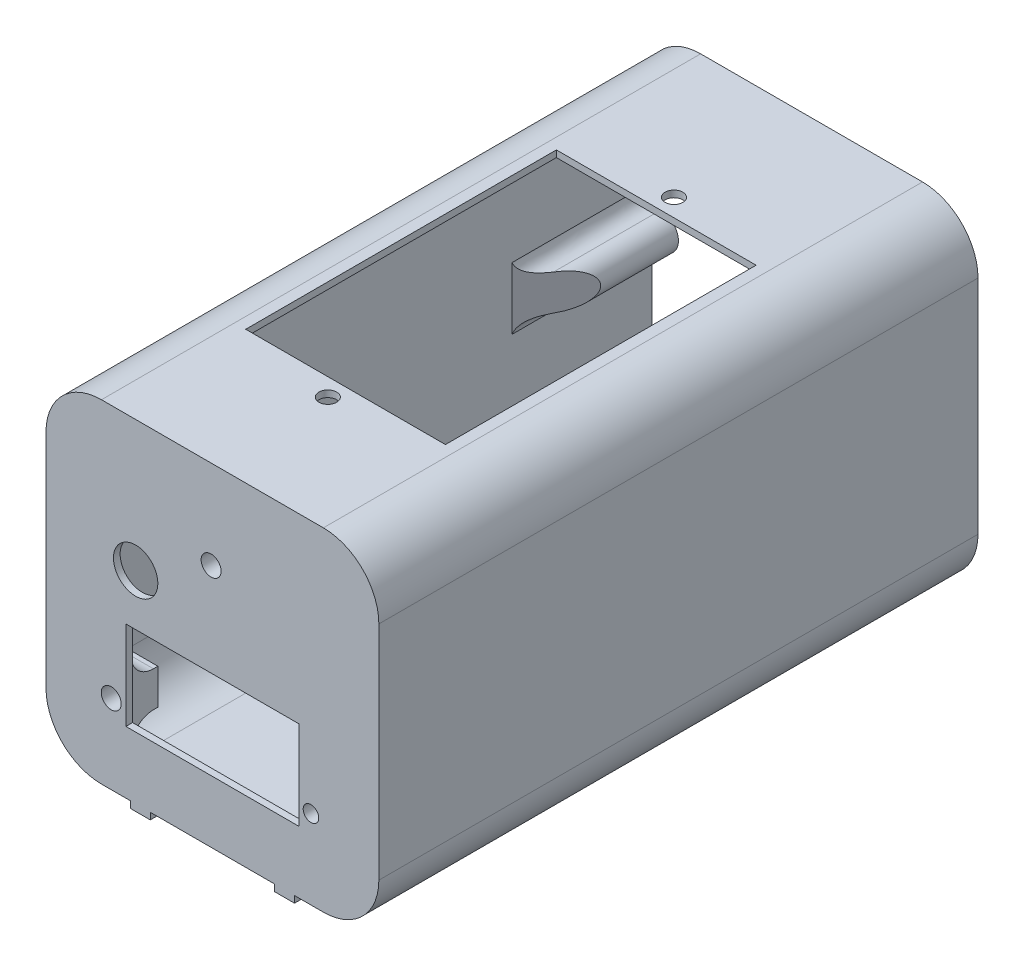
SolidWorks part; units mm, degrees
ref_plane "Front Plane" through (0, 0, 0) normal (0, 0, 1) x (1, 0, 0)
ref_plane "Top Plane" through (0, 0, 0) normal (0, 1, 0) x (1, 0, 0)
ref_plane "Right Plane" through (0, 0, 0) normal (1, 0, 0) x (0, 0, -1)
sketch "Sketch1" plane through (0, 0, 0) normal (0, 0, 1) x (1, 0, 0)
  line L0 (25.3, -11.5) -> (25.3, 2.5) construction
  line L1 (5.8, 2.5) -> (44.8, 2.5)
  line L2 (5.8, 2.5) -> (5.8, 22.5)
  line L3 (5.8, 22.5) -> (44.8, 22.5)
  line L4 (44.8, 2.5) -> (44.8, 22.5)
  line L5 (50.3, -11.5) -> (0.3, -11.5)
  line L6 (62.8, 1) -> (62.8, 51)
  line L7 (50.3, 63.5) -> (0.3, 63.5)
  line L8 (-12.2, 1) -> (-12.2, 51)
  circle A0 centre (8, 34) radius 5
  arc A1 (0.3, -11.5) -> (-12.2, 1) centre (0.3, 1) cw
  arc A2 (50.3, -11.5) -> (62.8, 1) centre (50.3, 1) ccw
  arc A3 (62.8, 51) -> (50.3, 63.5) centre (50.3, 51) ccw
  arc A4 (0.3, 63.5) -> (-12.2, 51) centre (0.3, 51) ccw
  point P15 (-12.2, -11.5)
  point P18 (62.8, -11.5)
  point P21 (62.8, 63.5)
  dimension "D3" = 10
  dimension "D6" = 34
  dimension "D7" = 8
  dimension "D10" = 12.5
  dimension "D1" = 20
  dimension "D2" = 39
  dimension "D4" = 5.8
  dimension "D5" = 2.5
  dimension "D8" = 75
  dimension "D9" = 75
  dimension "D11" = 11.5
extrude "Boss-Extrude1" add sketch "Sketch1" along normal blind 1.5
sketch "Sketch3" plane through (0, 0, 0) normal (0, 0, -1) x (-1, 0, 0)
  line L4 (-50.3, 63.5) -> (-0.3, 63.5) construction
  line L5 (12.2, 51) -> (12.2, 1) construction
  line L6 (-0.3, -11.5) -> (-50.3, -11.5) construction
  line L7 (-62.8, 1) -> (-62.8, 51) construction
  line L8 (10.7, 1) -> (10.7, 51)
  line L9 (-0.3, 62) -> (-50.3, 62)
  line L10 (-61.3, 51) -> (-61.3, 1)
  line L11 (-50.3, -10) -> (-0.3, -10)
  line L12 (10.7, 1) -> (10.7, 51)
  line L13 (-0.3, 62) -> (-50.3, 62)
  line L14 (-61.3, 51) -> (-61.3, 1)
  line L15 (-50.3, -10) -> (-0.3, -10)
  line L16 (-50.3, 63.5) -> (-0.3, 63.5)
  line L17 (12.2, 51) -> (12.2, 1)
  line L18 (-0.3, -11.5) -> (-50.3, -11.5)
  line L19 (-62.8, 1) -> (-62.8, 51)
  arc A4 (-50.3, 63.5) -> (-62.8, 51) centre (-50.3, 51) ccw construction
  arc A5 (12.2, 51) -> (-0.3, 63.5) centre (-0.3, 51) ccw construction
  arc A6 (-0.3, -11.5) -> (12.2, 1) centre (-0.3, 1) ccw construction
  arc A7 (-62.8, 1) -> (-50.3, -11.5) centre (-50.3, 1) ccw construction
  arc A8 (-0.3, -10) -> (10.7, 1) centre (-0.3, 1) ccw
  arc A9 (10.7, 51) -> (-0.3, 62) centre (-0.3, 51) ccw
  arc A10 (-50.3, 62) -> (-61.3, 51) centre (-50.3, 51) ccw
  arc A11 (-61.3, 1) -> (-50.3, -10) centre (-50.3, 1) ccw
  arc A12 (-0.3, -10) -> (10.7, 1) centre (-0.3, 1) ccw
  arc A13 (10.7, 51) -> (-0.3, 62) centre (-0.3, 51) ccw
  arc A14 (-50.3, 62) -> (-61.3, 51) centre (-50.3, 51) ccw
  arc A15 (-61.3, 1) -> (-50.3, -10) centre (-50.3, 1) ccw
  arc A16 (-50.3, 63.5) -> (-62.8, 51) centre (-50.3, 51) ccw
  arc A17 (12.2, 51) -> (-0.3, 63.5) centre (-0.3, 51) ccw
  arc A18 (-0.3, -11.5) -> (12.2, 1) centre (-0.3, 1) ccw
  arc A19 (-62.8, 1) -> (-50.3, -11.5) centre (-50.3, 1) ccw
  dimension "D1" = 1.5
extrude "Boss-Extrude3" add sketch "Sketch3" along normal blind 133.5
ref_plane "Plane1" through (0, 0, -132) normal (0, 0, -1) x (-1, 0, 0)
sketch "Sketch4" plane through (0, 0, -132) normal (0, 0, -1) x (-1, 0, 0)
  line L0 (-61.3, 51) -> (-61.3, 1) construction
  line L1 (-57.8, 26) -> (-16.2965, 26) construction
  line L2 (-25.3, 63.5) -> (-25.3, -2) construction
  line L3 (-0.3, 63.5) -> (-50.3, 63.5) construction
  line L5 (-61.3, 33) -> (-61.3, 19)
  line L6 (10.7, 33) -> (10.7, 19)
  arc A0 (-57.8, 22) -> (-57.8, 30) centre (-57.8, 26) ccw
  circle A1 centre (-57.8, 26) radius 2 construction
  arc A2 (7.2, 22) -> (7.2, 30) centre (7.2, 26) cw
  spline S0 degree 2 poles (-57.8, 30) (-60.736, 30.2111) (-61.3, 33) knots 0 0 0 1 1 1
  spline S1 degree 2 poles (-57.8, 22) (-60.736, 21.7889) (-61.3, 19) knots 0 0 0 1 1 1
  spline S2 degree 2 poles (7.2, 22) (10.136, 21.7889) (10.7, 19) knots 0 0 0 1 1 1
  spline S3 degree 2 poles (7.2, 30) (10.136, 30.2111) (10.7, 33) knots 0 0 0 1 1 1
  dimension "D1" = 8
  dimension "D4" = 2.5
  dimension "D2" = 7
  dimension "D3" = 5
extrude "Boss-Extrude4" add sketch "Sketch4" against normal blind 30
ref_plane "Plane2" through (0, 33, 0) normal (0, -1, 0) x (-1, 0, 0)
sketch "Sketch5" plane through (0, 33, 0) normal (0, -1, 0) x (-1, 0, 0)
  line L0 (10.7, 102) -> (3.2, 102)
  line L2 (3.2, 102) -> (3.2, 114.5)
  line L3 (3.2, 132) -> (3.2, 102) construction
  line L4 (3.2, 114.5) -> (10.7, 102)
  dimension "D1" = 12.5
  dimension "D2" = 7.5
extrude "Cut-Extrude1" cut sketch "Sketch5" along normal blind 15
sketch "Sketch6" plane through (0, 33, 0) normal (0, -1, 0) x (-1, 0, 0)
  line L0 (-61.3, 102) -> (-53.8, 102)
  line L1 (-53.8, 102) -> (-53.8, 114.5)
  line L2 (-53.8, 102) -> (-53.8, 132) construction
  line L3 (-53.8, 114.5) -> (-61.3, 102)
  dimension "D1" = 12.5
extrude "Cut-Extrude2" cut sketch "Sketch6" along normal blind 15
sketch "Sketch7" plane through (0, 0, -132) normal (0, 0, -1) x (-1, 0, 0)
  circle A0 centre (-57.8, 26) radius 2
  circle A1 centre (7.2, 26) radius 2
  dimension "D1" = 4
  dimension "D2" = 4
extrude "Cut-Extrude3" cut sketch "Sketch7" against normal blind 15
sketch "Sketch10" plane through (0, 63.5, 0) normal (0, 1, 0) x (1, 0, 0)
  line L0 (-12.2, -1.5) -> (-12.2, 133.5) construction
  line L1 (2.8, 98.5) -> (47.8, 98.5)
  line L2 (2.8, 98.5) -> (2.8, 28.5)
  line L3 (2.8, 28.5) -> (47.8, 28.5)
  line L4 (47.8, 98.5) -> (47.8, 28.5)
  line L5 (50.3, -1.5) -> (0.3, -1.5) construction
  dimension "D1" = 45
  dimension "D2" = 70
  dimension "D3" = 15
  dimension "D4" = 30
extrude "Cut-Extrude4" cut sketch "Sketch10" against normal blind 1.5
sketch "Sketch11" plane through (0, 63.5, 0) normal (0, 1, 0) x (1, 0, 0)
  circle A2 centre (25.3, 102.5) radius 2 construction
  circle A3 centre (25.3, 102.5) radius 2
  circle A4 centre (25.3, 24.5) radius 2 construction
  circle A5 centre (25.3, 24.5) radius 2
extrude "Cut-Extrude6" cut sketch "Sketch11" against normal blind 1.5
sketch "Sketch15" plane through (0, 0, 0) normal (0, 0, 1) x (1, 0, 0)
  line L1 (21, 47.5) -> (28, 47.5)
  line L2 (21, 47.5) -> (21, 40.5)
  line L3 (21, 40.5) -> (28, 40.5)
  line L4 (28, 47.5) -> (28, 40.5)
  line L5 (51.5, 10.35) -> (45.6, 10.35)
  line L6 (51.5, 10.35) -> (51.5, 2.35)
  line L7 (51.5, 2.35) -> (45.6, 2.35)
  line L8 (45.6, 10.35) -> (45.6, 2.35)
  line L9 (-1.5, 10.35) -> (5.5, 10.35)
  line L10 (-1.5, 10.35) -> (-1.5, 2.35)
  line L11 (-1.5, 2.35) -> (5.5, 2.35)
  line L12 (5.5, 10.35) -> (5.5, 2.35)
  circle A0 centre (25, 43.5) radius 1.15 construction
  circle A1 centre (47.5, 6.35) radius 1.15 construction
  circle A2 centre (2.5, 6.35) radius 1.15 construction
  dimension "D1" = 3
  dimension "D2" = 4
  dimension "D3" = 3
  dimension "D4" = 4
  dimension "D5" = 1.9
  dimension "D6" = 4
  dimension "D7" = 4
  dimension "D8" = 4
  dimension "D9" = 4
  dimension "D10" = 3
  dimension "D11" = 4
  dimension "D12" = 4
extrude "Boss-Extrude5" add sketch "Sketch15" against normal blind 6
sketch "Sketch16" plane through (0, 0, 1.5) normal (0, 0, 1) x (1, 0, 0)
  circle A0 centre (2.5, 6.35) radius 1.15 construction
  circle A2 centre (25, 43.5) radius 1.15
  circle A3 centre (47.5, 6.35) radius 1.15 construction
  circle A4 centre (25, 43.5) radius 1.15 construction
  circle A12 centre (2.5, 6.35) radius 1.15 construction
  circle A13 centre (47.5, 6.35) radius 1.15 construction
  circle A14 centre (25, 43.5) radius 2.25
  circle A15 centre (47.5, 6.35) radius 1.75
  circle A16 centre (2.5, 6.35) radius 2.25
  dimension "D3" = 4.5
  dimension "D4" = 3.5
  dimension "D5" = 4.5
  dimension "D2" = 0
extrude "Cut-Extrude20" cut sketch "Sketch16" against normal blind 10
fillet "Fillet5" radius 5 3 edges at (-1.5, 6.35, 0) (2, 2.35, 0) (2, 10.35, 0)
fillet "Fillet6" radius 5 3 edges at (48.55, 2.35, 0) (51.5, 6.35, 0) (48.55, 10.35, 0)
fillet "Fillet7" radius 5 4 edges at (24.5, 47.5, 0) (28, 44, 0) (24.5, 40.5, 0) (21, 44, 0)
sketch "Sketch17" plane through (0, 0, 1.5) normal (0, 0, 1) x (1, 0, 0)
  line L0 (25.3, -11.5) -> (25.3, -19.0097) construction
  line L1 (0.3, -11.5) -> (50.3, -11.5) construction
  line L2 (39.3, -11.5) -> (39.3, -13)
  line L3 (6.8, -11.5) -> (11.3, -11.5)
  line L4 (6.8, -11.5) -> (6.8, -13)
  line L5 (6.8, -13) -> (11.3, -13)
  line L6 (11.3, -11.5) -> (11.3, -13)
  line L7 (43.8, -13) -> (39.3, -13)
  line L8 (43.8, -11.5) -> (43.8, -13)
  line M9 (0.3, -11.5) -> (50.3, -11.5)
  dimension "D1" = 1.5
  dimension "D2" = 4.5
  dimension "D3" = 14
extrude "Boss-Extrude6" add sketch "Sketch17" against normal up to surface (135 mm away) contours L8 L2 L7 M9 | L6 L4 L5 M9 up to face at (25.3, 26, -133.5)
